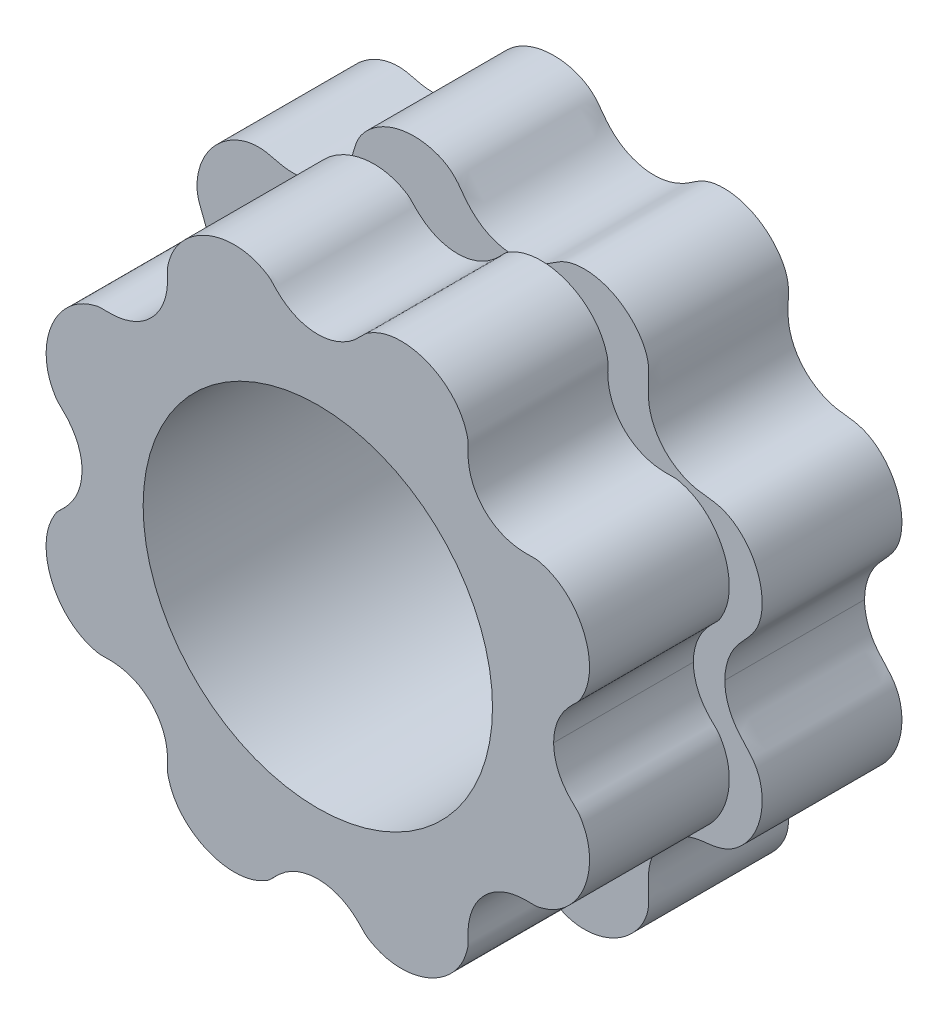
SolidWorks part; units mm, degrees
ref_plane "Plan de face" through (0, 0, 0) normal (0, 0, 1) x (1, 0, 0)
ref_plane "Plan de dessus" through (0, 0, 0) normal (0, 1, 0) x (1, 0, 0)
ref_plane "Plan de droite" through (0, 0, 0) normal (1, 0, 0) x (0, 0, -1)
sketch "Esquisse1" plane through (0, 0, 0) normal (0, 0, 1) x (1, 0, 0)
  line L0 (-1000, 0) -> (49000, 0) construction
  spline S0 degree 4 poles (8.7803, 2.0844) (8.759, 1.978) (8.7116, 1.8178) (8.6208, 1.6087) (8.4352, 1.3623) (8.2291, 1.1723) (8.0546, 0.9611) (7.9309, 0.754) (7.8577, 0.5838) (7.8163, 0.4608) (7.7897, 0.3601) (7.7696, 0.2597) (7.7562, 0.1563) (7.7491, 0.0328) (7.7496, -0.0491) (7.7588, -0.1913) (7.7779, -0.3065) (7.8056, -0.4254) (7.841, -0.5373) (7.8831, -0.6437) (7.9405, -0.7643) (8.0051, -0.8752) (8.0749, -0.9763) (8.1479, -1.0682) (8.2211, -1.1528) (8.3136, -1.2502) (8.4331, -1.3675) (8.5597, -1.5239) (8.6668, -1.7139) (8.7499, -1.9332) (8.8131, -2.2165) (8.8306, -2.5628) (8.778, -2.9416) (8.6388, -3.3355) (8.4213, -3.7041) (8.1416, -4.0116) (7.8245, -4.2297) (7.4913, -4.3566) (7.1957, -4.385) (6.9323, -4.4107) (6.6448, -4.4834) (6.3462, -4.6152) (6.0562, -4.8275) (5.8056, -5.1258) (5.6474, -5.4483) (5.5685, -5.7654) (5.5509, -6.0274) (5.559, -6.2259) (5.5768, -6.424) (5.5841, -6.6544) (5.5247, -6.9709) (5.364, -7.3215) (5.1104, -7.6501) (4.7959, -7.9189) (4.46, -8.1128) (4.07, -8.2508) (3.6586, -8.3061) (3.2746, -8.27) (2.9708, -8.1632) (2.775, -8.0416) (2.6123, -7.9272) (2.4444, -7.8209) (2.2088, -7.7052) (1.8946, -7.6149) (1.5364, -7.5907) (1.1524, -7.6584) (0.8241, -7.8037) (0.5597, -7.996) (0.3779, -8.1853) (0.2565, -8.3426) (0.1428, -8.5058) (0.0003, -8.687) (-0.2486, -8.8913) (-0.5971, -9.0565) (-1.0026, -9.1453) (-1.4163, -9.149) (-1.7983, -9.0816) (-2.1858, -8.9366) (-2.5365, -8.7145) (-2.8074, -8.4401) (-2.9714, -8.1629) (-3.0433, -7.944) (-3.0944, -7.7517) (-3.1547, -7.5624) (-3.2608, -7.3223) (-3.4435, -7.0512) (-3.7022, -6.8024) (-4.04, -6.6075) (-4.3848, -6.5077) (-4.711, -6.4851) (-4.9719, -6.5132) (-5.166, -6.5557) (-5.358, -6.6076) (-5.5836, -6.6548) (-5.9057, -6.6513) (-6.2788, -6.5539) (-6.6465, -6.3612) (-6.9658, -6.0981) (-7.2151, -5.801) (-7.4187, -5.4409) (-7.5446, -5.0453) (-7.5758, -4.661) (-7.5233, -4.3432) (-7.4376, -4.1292) (-7.3531, -3.9491) (-7.2776, -3.7654) (-7.2046, -3.5133) (-7.1703, -3.1881) (-7.2096, -2.8216) (-7.3528, -2.4379) (-7.5822, -2.113) (-7.8731, -1.8612) (-8.1648, -1.6988) (-8.4272, -1.5882) (-8.635, -1.4411) (-8.7928, -1.2863) (-8.9216, -1.1185) (-9.0241, -0.9478) (-9.1056, -0.7696) (-9.1676, -0.5968) (-9.2112, -0.4121) (-9.2383, -0.2591) (-9.2499, -0.0714) (-9.2511, 0.0231) (-9.2456, 0.1474) (-9.236, 0.2528) (-9.2216, 0.3507) (-9.2023, 0.4489) (-9.1722, 0.5713) (-9.1226, 0.7275) (-9.0436, 0.9139) (-8.9291, 1.1109) (-8.7889, 1.2906) (-8.642, 1.4324) (-8.4961, 1.5394) (-8.3465, 1.6201) (-8.2018, 1.6867) (-8.0955, 1.7412) (-8.0264, 1.7808) (-7.9923, 1.8014) knots 0 0 0 0 0 0.012017 0.018525 0.025033 0.034045 0.043057 0.048815 0.051694 0.054573 0.057453 0.060333 0.063213 0.066093 0.069526 0.072959 0.076393 0.079826 0.08291 0.085994 0.089079 0.094647 0.097131 0.099614 0.102098 0.107066 0.112033 0.118191 0.124349 0.131165 0.13798 0.150298 0.162615 0.173316 0.184016 0.19759 0.208293 0.215687 0.22308 0.230394 0.237707 0.24842 0.259137 0.269855 0.280567 0.287881 0.295194 0.298891 0.302588 0.309981 0.320684 0.334258 0.344959 0.355659 0.36636 0.37706 0.390635 0.401338 0.408731 0.412428 0.416125 0.423438 0.430751 0.441464 0.452182 0.462899 0.473612 0.480925 0.488239 0.491935 0.495632 0.503026 0.513729 0.527303 0.538003 0.548704 0.559404 0.570105 0.583679 0.594382 0.601775 0.605472 0.609169 0.616482 0.623796 0.634508 0.645226 0.655944 0.666656 0.67397 0.681283 0.68498 0.688676 0.69607 0.706773 0.720347 0.731048 0.741748 0.752449 0.763149 0.776723 0.787426 0.79482 0.798517 0.802213 0.809527 0.81684 0.827553 0.83827 0.850051 0.861806 0.871198 0.880589 0.886967 0.893346 0.899224 0.905101 0.910307 0.915512 0.920718 0.925923 0.930358 0.934792 0.937583 0.940373 0.943163 0.945953 0.948743 0.951534 0.957114 0.964137 0.97116 0.976742 0.982324 0.986743 0.991162 0.995581 1 1 1 1 1 construction
  spline S1 degree 4 poles (7.75, 0) (7.75, -0.0269) (7.7516, -0.0801) (7.7588, -0.1913) (7.7779, -0.3065) (7.8056, -0.4254) (7.841, -0.5373) (7.8831, -0.6437) (7.9405, -0.7643) (8.0051, -0.8752) (8.0749, -0.9763) (8.1479, -1.0682) (8.2211, -1.1528) (8.3136, -1.2502) (8.4331, -1.3675) (8.5597, -1.5239) (8.6668, -1.7139) (8.7499, -1.9332) (8.8131, -2.2165) (8.8306, -2.5628) (8.778, -2.9416) (8.6388, -3.3355) (8.4213, -3.7041) (8.1416, -4.0116) (7.8245, -4.2297) (7.4913, -4.3566) (7.1957, -4.385) (6.9323, -4.4107) (6.6448, -4.4834) (6.3462, -4.6152) (6.0562, -4.8275) (5.8056, -5.1258) (5.6474, -5.4483) (5.5685, -5.7654) (5.5509, -6.0274) (5.559, -6.2259) (5.5768, -6.424) (5.5841, -6.6544) (5.5247, -6.9709) (5.364, -7.3215) (5.1104, -7.6501) (4.7959, -7.9189) (4.46, -8.1128) (4.07, -8.2508) (3.6586, -8.3061) (3.2746, -8.27) (2.9708, -8.1632) (2.775, -8.0416) (2.6123, -7.9272) (2.4444, -7.8209) (2.2088, -7.7052) (1.8946, -7.6149) (1.5364, -7.5907) (1.1524, -7.6584) (0.8241, -7.8037) (0.5597, -7.996) (0.3779, -8.1853) (0.2565, -8.3426) (0.1428, -8.5058) (0.0003, -8.687) (-0.2486, -8.8913) (-0.5971, -9.0565) (-1.0026, -9.1453) (-1.4163, -9.149) (-1.7983, -9.0816) (-2.1858, -8.9366) (-2.5365, -8.7145) (-2.8074, -8.4401) (-2.9714, -8.1629) (-3.0433, -7.944) (-3.0944, -7.7517) (-3.1547, -7.5624) (-3.2608, -7.3223) (-3.4435, -7.0512) (-3.7022, -6.8024) (-4.04, -6.6075) (-4.3848, -6.5077) (-4.711, -6.4851) (-4.9719, -6.5132) (-5.166, -6.5557) (-5.358, -6.6076) (-5.5836, -6.6548) (-5.9057, -6.6513) (-6.2788, -6.5539) (-6.6465, -6.3612) (-6.9658, -6.0981) (-7.2151, -5.801) (-7.4187, -5.4409) (-7.5446, -5.0453) (-7.5758, -4.661) (-7.5233, -4.3432) (-7.4376, -4.1292) (-7.3531, -3.9491) (-7.2776, -3.7654) (-7.2046, -3.5133) (-7.1703, -3.1881) (-7.2096, -2.8216) (-7.3528, -2.4379) (-7.5822, -2.113) (-7.8731, -1.8612) (-8.1648, -1.6988) (-8.4272, -1.5882) (-8.635, -1.4411) (-8.7928, -1.2863) (-8.9216, -1.1185) (-9.0241, -0.9478) (-9.1056, -0.7696) (-9.1676, -0.5968) (-9.2112, -0.4121) (-9.2383, -0.2591) (-9.248, -0.1025) (-9.25, -0.0347) (-9.25, 0) knots 0.066093 0.066093 0.066093 0.066093 0.066093 0.069526 0.072959 0.076393 0.079826 0.08291 0.085994 0.089079 0.094647 0.097131 0.099614 0.102098 0.107066 0.112033 0.118191 0.124349 0.131165 0.13798 0.150298 0.162615 0.173316 0.184016 0.19759 0.208293 0.215687 0.22308 0.230394 0.237707 0.24842 0.259137 0.269855 0.280567 0.287881 0.295194 0.298891 0.302588 0.309981 0.320684 0.334258 0.344959 0.355659 0.36636 0.37706 0.390635 0.401338 0.408731 0.412428 0.416125 0.423438 0.430751 0.441464 0.452182 0.462899 0.473612 0.480925 0.488239 0.491935 0.495632 0.503026 0.513729 0.527303 0.538003 0.548704 0.559404 0.570105 0.583679 0.594382 0.601775 0.605472 0.609169 0.616482 0.623796 0.634508 0.645226 0.655944 0.666656 0.67397 0.681283 0.68498 0.688676 0.69607 0.706773 0.720347 0.731048 0.741748 0.752449 0.763149 0.776723 0.787426 0.79482 0.798517 0.802213 0.809527 0.81684 0.827553 0.83827 0.850051 0.861806 0.871198 0.880589 0.886967 0.893346 0.899224 0.905101 0.910307 0.915512 0.920718 0.925923 0.930358 0.934792 0.934792 0.934792 0.934792 0.934792 construction
  spline S2 degree 4 poles (7.75, 0) (7.75, 0.0269) (7.7516, 0.0801) (7.7588, 0.1913) (7.7779, 0.3065) (7.8056, 0.4254) (7.841, 0.5373) (7.8831, 0.6437) (7.9405, 0.7643) (8.0051, 0.8752) (8.0749, 0.9763) (8.1479, 1.0682) (8.2211, 1.1528) (8.3136, 1.2502) (8.4331, 1.3675) (8.5597, 1.5239) (8.6668, 1.7139) (8.7499, 1.9332) (8.8131, 2.2165) (8.8306, 2.5628) (8.778, 2.9416) (8.6388, 3.3355) (8.4213, 3.7041) (8.1416, 4.0116) (7.8245, 4.2297) (7.4913, 4.3566) (7.1957, 4.385) (6.9323, 4.4107) (6.6448, 4.4834) (6.3462, 4.6152) (6.0562, 4.8275) (5.8056, 5.1258) (5.6474, 5.4483) (5.5685, 5.7654) (5.5509, 6.0274) (5.559, 6.2259) (5.5768, 6.424) (5.5841, 6.6544) (5.5247, 6.9709) (5.364, 7.3215) (5.1104, 7.6501) (4.7959, 7.9189) (4.46, 8.1128) (4.07, 8.2508) (3.6586, 8.3061) (3.2746, 8.27) (2.9708, 8.1632) (2.775, 8.0416) (2.6123, 7.9272) (2.4444, 7.8209) (2.2088, 7.7052) (1.8946, 7.6149) (1.5364, 7.5907) (1.1524, 7.6584) (0.8241, 7.8037) (0.5597, 7.996) (0.3779, 8.1853) (0.2565, 8.3426) (0.1428, 8.5058) (0.0003, 8.687) (-0.2486, 8.8913) (-0.5971, 9.0565) (-1.0026, 9.1453) (-1.4163, 9.149) (-1.7983, 9.0816) (-2.1858, 8.9366) (-2.5365, 8.7145) (-2.8074, 8.4401) (-2.9714, 8.1629) (-3.0433, 7.944) (-3.0944, 7.7517) (-3.1547, 7.5624) (-3.2608, 7.3223) (-3.4435, 7.0512) (-3.7022, 6.8024) (-4.04, 6.6075) (-4.3848, 6.5077) (-4.711, 6.4851) (-4.9719, 6.5132) (-5.166, 6.5557) (-5.358, 6.6076) (-5.5836, 6.6548) (-5.9057, 6.6513) (-6.2788, 6.5539) (-6.6465, 6.3612) (-6.9658, 6.0981) (-7.2151, 5.801) (-7.4187, 5.4409) (-7.5446, 5.0453) (-7.5758, 4.661) (-7.5233, 4.3432) (-7.4376, 4.1292) (-7.3531, 3.9491) (-7.2776, 3.7654) (-7.2046, 3.5133) (-7.1703, 3.1881) (-7.2096, 2.8216) (-7.3528, 2.4379) (-7.5822, 2.113) (-7.8731, 1.8612) (-8.1648, 1.6988) (-8.4272, 1.5882) (-8.635, 1.4411) (-8.7928, 1.2863) (-8.9216, 1.1185) (-9.0241, 0.9478) (-9.1056, 0.7696) (-9.1676, 0.5968) (-9.2112, 0.4121) (-9.2383, 0.2591) (-9.248, 0.1025) (-9.25, 0.0347) (-9.25, 0) knots 0.066093 0.066093 0.066093 0.066093 0.066093 0.069526 0.072959 0.076393 0.079826 0.08291 0.085994 0.089079 0.094647 0.097131 0.099614 0.102098 0.107066 0.112033 0.118191 0.124349 0.131165 0.13798 0.150298 0.162615 0.173316 0.184016 0.19759 0.208293 0.215687 0.22308 0.230394 0.237707 0.24842 0.259137 0.269855 0.280567 0.287881 0.295194 0.298891 0.302588 0.309981 0.320684 0.334258 0.344959 0.355659 0.36636 0.37706 0.390635 0.401338 0.408731 0.412428 0.416125 0.423438 0.430751 0.441464 0.452182 0.462899 0.473612 0.480925 0.488239 0.491935 0.495632 0.503026 0.513729 0.527303 0.538003 0.548704 0.559404 0.570105 0.583679 0.594382 0.601775 0.605472 0.609169 0.616482 0.623796 0.634508 0.645226 0.655944 0.666656 0.67397 0.681283 0.68498 0.688676 0.69607 0.706773 0.720347 0.731048 0.741748 0.752449 0.763149 0.776723 0.787426 0.79482 0.798517 0.802213 0.809527 0.81684 0.827553 0.83827 0.850051 0.861806 0.871198 0.880589 0.886967 0.893346 0.899224 0.905101 0.910307 0.915512 0.920718 0.925923 0.930358 0.934792 0.934792 0.934792 0.934792 0.934792 construction
  spline S3 degree 1 poles (7.65, 0) (-9.15, 0) knots 0 0 1 1 construction
  spline S4 degree 1 poles (7.65, 0) (-9.15, 0) knots 0 0 1 1 construction
  spline S5 degree 3 poles (7.65, 0) (7.65, 0.3408) (7.8098, 0.8699) (8.2973, 1.3646) (8.6717, 1.828) (8.7831, 2.6376) (8.5305, 3.3888) (8.1407, 3.8756) (7.7627, 4.1565) (7.3383, 4.2872) (6.6589, 4.3181) (5.8584, 4.7576) (5.453, 5.5666) (5.4572, 6.2693) (5.5047, 6.879) (5.1067, 7.5875) (4.4533, 8.036) (3.848, 8.1914) (3.3794, 8.1898) (2.9459, 8.0584) (2.5618, 7.7538) (2.0783, 7.5424) (1.383, 7.4623) (0.7011, 7.7054) (0.2114, 8.2113) (-0.1292, 8.7502) (-0.8552, 9.0773) (-1.6511, 9.0424) (-2.2286, 8.802) (-2.6017, 8.5215) (-2.8866, 8.1566) (-2.9939, 7.7006) (-3.1913, 7.2112) (-3.6388, 6.6728) (-4.2986, 6.3773) (-5.0016, 6.3971) (-5.4766, 6.5533) (-5.925, 6.5512) (-6.52, 6.3553) (-7.0089, 5.9463) (-7.3258, 5.4066) (-7.4571, 4.9596) (-7.4718, 4.4901) (-7.3011, 4.0739) (-7.1001, 3.5882) (-7.0658, 3.0647) (-7.1841, 2.5522) (-7.4539, 2.1016) (-7.8414, 1.7461) (-8.3141, 1.5373) (-8.6819, 1.2898) (-9.0415, 0.7761) (-9.15, 0.307) (-9.15, 0) knots 0.066093 0.066093 0.066093 0.066093 0.09324 0.106813 0.120387 0.147533 0.17468 0.188254 0.201827 0.215401 0.228974 0.256121 0.283268 0.296841 0.310415 0.337561 0.364708 0.378282 0.391855 0.405429 0.419002 0.432576 0.446149 0.473296 0.486869 0.500443 0.52759 0.554736 0.56831 0.581883 0.595457 0.60903 0.622604 0.636177 0.663324 0.676897 0.690471 0.704044 0.717618 0.744764 0.758338 0.771911 0.785485 0.799058 0.812632 0.826205 0.839778 0.853352 0.866925 0.880499 0.894072 0.907646 0.934792 0.934792 0.934792 0.934792
  spline S6 degree 3 poles (-9.15, 0) (-9.15, -0.307) (-9.0415, -0.7761) (-8.6819, -1.2898) (-8.3141, -1.5373) (-7.8414, -1.7461) (-7.4539, -2.1016) (-7.1841, -2.5522) (-7.0658, -3.0647) (-7.1001, -3.5882) (-7.3011, -4.0739) (-7.4718, -4.4901) (-7.4571, -4.9596) (-7.3258, -5.4066) (-7.0089, -5.9463) (-6.52, -6.3553) (-5.925, -6.5512) (-5.4766, -6.5533) (-5.0016, -6.3971) (-4.2986, -6.3773) (-3.6388, -6.6728) (-3.1913, -7.2112) (-2.9939, -7.7006) (-2.8866, -8.1566) (-2.6017, -8.5215) (-2.2286, -8.802) (-1.6511, -9.0424) (-0.8552, -9.0773) (-0.1292, -8.7502) (0.2114, -8.2113) (0.7011, -7.7054) (1.383, -7.4623) (2.0783, -7.5424) (2.5618, -7.7538) (2.9459, -8.0584) (3.3794, -8.1898) (3.848, -8.1914) (4.4533, -8.036) (5.1067, -7.5875) (5.5047, -6.879) (5.4572, -6.2693) (5.453, -5.5666) (5.8584, -4.7576) (6.6589, -4.3181) (7.3383, -4.2872) (7.7627, -4.1565) (8.1407, -3.8756) (8.5305, -3.3888) (8.7831, -2.6376) (8.6717, -1.828) (8.2973, -1.3646) (7.8098, -0.8699) (7.65, -0.3408) (7.65, 0) knots 0.066093 0.066093 0.066093 0.066093 0.09324 0.106813 0.120387 0.13396 0.147533 0.161107 0.17468 0.188254 0.201827 0.215401 0.228974 0.242547 0.256121 0.283268 0.296841 0.310415 0.323988 0.337561 0.364708 0.378282 0.391855 0.405429 0.419002 0.432576 0.446149 0.473296 0.500443 0.514016 0.52759 0.554736 0.56831 0.581883 0.595457 0.60903 0.622604 0.636177 0.663324 0.690471 0.704044 0.717618 0.744764 0.771911 0.785485 0.799058 0.812632 0.826205 0.853352 0.880499 0.894072 0.907646 0.934792 0.934792 0.934792 0.934792
  dimension "D2" = 0.1
extrude "Boss.-Extru.4" add sketch "Esquisse1" along normal blind 4
sketch "Esquisse3" plane through (0, 0, 4) normal (0, 0, 1) x (1, 0, 0)
  line L0 (-1000, 0) -> (49000, 0) construction
  spline S0 degree 4 poles (7.6487, 1.7197) (7.6397, 1.6979) (7.6209, 1.6547) (7.5905, 1.5907) (7.5449, 1.5086) (7.4945, 1.4152) (7.4156, 1.3285) (7.3207, 1.2433) (7.2229, 1.1446) (7.1213, 1.0311) (7.022, 0.8979) (6.9433, 0.7673) (6.8836, 0.6419) (6.8431, 0.538) (6.8166, 0.4579) (6.7944, 0.3761) (6.7766, 0.2945) (6.7631, 0.2088) (6.7541, 0.1312) (6.7495, 0.0278) (6.7497, -0.0349) (6.755, -0.1463) (6.7659, -0.2288) (6.7823, -0.3252) (6.8041, -0.4141) (6.8312, -0.505) (6.8638, -0.5929) (6.9206, -0.7239) (7.0139, -0.8909) (7.1289, -1.0461) (7.2627, -1.1858) (7.368, -1.2868) (7.4406, -1.3539) (7.5056, -1.4337) (7.5559, -1.528) (7.6216, -1.6501) (7.6947, -1.8258) (7.7568, -2.0554) (7.7966, -2.4362) (7.7454, -2.8544) (7.5976, -3.2677) (7.3603, -3.6343) (7.1292, -3.8825) (6.911, -4.0477) (6.7294, -4.1486) (6.5829, -4.211) (6.4776, -4.2466) (6.3715, -4.2786) (6.2628, -4.3043) (6.1509, -4.3009) (6.0404, -4.2985) (5.9239, -4.2978) (5.8026, -4.3041) (5.6436, -4.3223) (5.4229, -4.3705) (5.155, -4.4742) (4.8654, -4.6639) (4.6419, -4.9004) (4.4944, -5.1337) (4.3922, -5.3665) (4.3272, -5.5934) (4.2993, -5.8053) (4.2972, -5.9963) (4.3013, -6.1603) (4.3052, -6.2826) (4.2677, -6.4051) (4.2302, -6.531) (4.1885, -6.638) (4.12, -6.7845) (4.0111, -6.9637) (3.787, -7.2391) (3.4519, -7.4995) (3.0502, -7.6876) (2.6199, -7.7764) (2.3177, -7.7846) (2.076, -7.7554) (1.9043, -7.7148) (1.7805, -7.6742) (1.6679, -7.6286) (1.5679, -7.5773) (1.4654, -7.524) (1.3669, -7.457) (1.2857, -7.3653) (1.1987, -7.277) (1.1097, -7.1899) (1.015, -7.1102) (0.9159, -7.0363) (0.8118, -6.9702) (0.6463, -6.8813) (0.41, -6.7909) (0.1026, -6.7349) (-0.2229, -6.7528) (-0.488, -6.8195) (-0.7192, -6.9154) (-0.8907, -7.015) (-1.0429, -7.1291) (-1.182, -7.2587) (-1.2787, -7.3583) (-1.3626, -7.4521) (-1.4589, -7.5196) (-1.5486, -7.567) (-1.6436, -7.6173) (-1.7485, -7.6619) (-1.9044, -7.7167) (-2.1159, -7.7653) (-2.4808, -7.7964) (-2.9052, -7.733) (-3.313, -7.5746) (-3.6656, -7.3338) (-3.8974, -7.1111) (-4.0687, -6.8803) (-4.1744, -6.6805) (-4.2373, -6.5108) (-4.2742, -6.3839) (-4.3003, -6.2855) (-4.3025, -6.1875) (-4.2996, -6.0941) (-4.2976, -5.9894) (-4.2995, -5.8738) (-4.3116, -5.7131) (-4.3434, -5.5336) (-4.3989, -5.3495) (-4.4996, -5.1248) (-4.6481, -4.8926) (-4.8426, -4.689) (-5.0764, -4.5257) (-5.316, -4.4107) (-5.5431, -4.3383) (-5.7566, -4.3039) (-5.9497, -4.2969) (-6.0992, -4.2993) (-6.2053, -4.3041) (-6.3143, -4.2957) (-6.4213, -4.2629) (-6.558, -4.222) (-6.7391, -4.1467) (-6.952, -4.0228) (-7.1878, -3.827) (-7.4065, -3.5709) (-7.5838, -3.2732) (-7.7111, -2.9408) (-7.7764, -2.6074) (-7.785, -2.284) (-7.7441, -1.9963) (-7.6775, -1.7765) (-7.6005, -1.6085) (-7.534, -1.4869) (-7.4778, -1.3922) (-7.3995, -1.3162) (-7.3222, -1.2428) (-7.2415, -1.1638) (-7.1612, -1.0767) (-7.0826, -0.9803) (-7.0081, -0.8737) (-6.947, -0.7706) (-6.898, -0.6726) (-6.8592, -0.5812) (-6.829, -0.4974) (-6.8032, -0.4111) (-6.7821, -0.3226) (-6.7659, -0.2313) (-6.755, -0.1423) (-6.7484, -0.0133) (-6.7502, 0.0591) (-6.7598, 0.2021) (-6.7799, 0.3082) (-6.8089, 0.4423) (-6.8572, 0.5815) (-6.9324, 0.751) (-7.022, 0.8967) (-7.1213, 1.0319) (-7.2229, 1.1442) (-7.3207, 1.2436) (-7.4156, 1.3284) (-7.4945, 1.4153) (-7.5449, 1.5086) (-7.5905, 1.5907) (-7.6209, 1.6547) (-7.6397, 1.6979) (-7.6487, 1.7197) knots 0 0 0 0 0 0.002971 0.005941 0.008912 0.011882 0.016256 0.02063 0.025004 0.029378 0.035458 0.041538 0.044198 0.046857 0.049517 0.052177 0.054837 0.057497 0.060158 0.062818 0.06575 0.068682 0.071614 0.074546 0.077511 0.080477 0.083443 0.086408 0.095483 0.104557 0.107667 0.110776 0.113886 0.116995 0.120592 0.124189 0.131384 0.140925 0.150466 0.172222 0.183937 0.195652 0.205212 0.214772 0.218272 0.221773 0.225273 0.228773 0.232271 0.235769 0.239267 0.242765 0.246927 0.25109 0.259415 0.271179 0.282914 0.294344 0.300072 0.3058 0.314901 0.324001 0.326913 0.329824 0.335648 0.339256 0.342863 0.34647 0.350078 0.359646 0.369213 0.391031 0.402991 0.414951 0.424282 0.428948 0.433613 0.437157 0.4407 0.444244 0.447788 0.451711 0.455635 0.459558 0.463482 0.467365 0.471248 0.47513 0.479013 0.49103 0.503006 0.514154 0.519741 0.525328 0.534497 0.539082 0.543666 0.549255 0.55205 0.554844 0.558433 0.562022 0.565611 0.5692 0.57925 0.5893 0.611553 0.62268 0.633806 0.642852 0.651897 0.658762 0.662195 0.665627 0.668578 0.671529 0.67448 0.677431 0.681767 0.686104 0.694778 0.700357 0.705936 0.717086 0.729368 0.735527 0.741686 0.750505 0.759325 0.76267 0.766015 0.769361 0.772706 0.776376 0.780045 0.787384 0.797351 0.807318 0.818484 0.829649 0.840815 0.85198 0.861108 0.870237 0.877296 0.880825 0.884355 0.887728 0.8911 0.894473 0.897846 0.901942 0.906038 0.910135 0.914231 0.917037 0.919843 0.922648 0.925454 0.928386 0.931318 0.93425 0.937182 0.942503 0.945163 0.947823 0.953143 0.958462 0.964542 0.970622 0.974996 0.97937 0.983744 0.988118 0.991088 0.994059 0.997029 1 1 1 1 1 construction
  spline S1 degree 4 poles (6.75, 0) (6.75, -0.0203) (6.7509, -0.0607) (6.755, -0.1463) (6.7659, -0.2288) (6.7823, -0.3252) (6.8041, -0.4141) (6.8312, -0.505) (6.8638, -0.5929) (6.9206, -0.7239) (7.0139, -0.8909) (7.1289, -1.0461) (7.2627, -1.1858) (7.368, -1.2868) (7.4406, -1.3539) (7.5056, -1.4337) (7.5559, -1.528) (7.6216, -1.6501) (7.6947, -1.8258) (7.7568, -2.0554) (7.7966, -2.4362) (7.7454, -2.8544) (7.5976, -3.2677) (7.3603, -3.6343) (7.1292, -3.8825) (6.911, -4.0477) (6.7294, -4.1486) (6.5829, -4.211) (6.4776, -4.2466) (6.3715, -4.2786) (6.2628, -4.3043) (6.1509, -4.3009) (6.0404, -4.2985) (5.9239, -4.2978) (5.8026, -4.3041) (5.6436, -4.3223) (5.4229, -4.3705) (5.155, -4.4742) (4.8654, -4.6639) (4.6419, -4.9004) (4.4944, -5.1337) (4.3922, -5.3665) (4.3272, -5.5934) (4.2993, -5.8053) (4.2972, -5.9963) (4.3013, -6.1603) (4.3052, -6.2826) (4.2677, -6.4051) (4.2302, -6.531) (4.1885, -6.638) (4.12, -6.7845) (4.0111, -6.9637) (3.787, -7.2391) (3.4519, -7.4995) (3.0502, -7.6876) (2.6199, -7.7764) (2.3177, -7.7846) (2.076, -7.7554) (1.9043, -7.7148) (1.7805, -7.6742) (1.6679, -7.6286) (1.5679, -7.5773) (1.4654, -7.524) (1.3669, -7.457) (1.2857, -7.3653) (1.1987, -7.277) (1.1097, -7.1899) (1.015, -7.1102) (0.9159, -7.0363) (0.8118, -6.9702) (0.6463, -6.8813) (0.41, -6.7909) (0.1026, -6.7349) (-0.2229, -6.7528) (-0.488, -6.8195) (-0.7192, -6.9154) (-0.8907, -7.015) (-1.0429, -7.1291) (-1.182, -7.2587) (-1.2787, -7.3583) (-1.3626, -7.4521) (-1.4589, -7.5196) (-1.5486, -7.567) (-1.6436, -7.6173) (-1.7485, -7.6619) (-1.9044, -7.7167) (-2.1159, -7.7653) (-2.4808, -7.7964) (-2.9052, -7.733) (-3.313, -7.5746) (-3.6656, -7.3338) (-3.8974, -7.1111) (-4.0687, -6.8803) (-4.1744, -6.6805) (-4.2373, -6.5108) (-4.2742, -6.3839) (-4.3003, -6.2855) (-4.3025, -6.1875) (-4.2996, -6.0941) (-4.2976, -5.9894) (-4.2995, -5.8738) (-4.3116, -5.7131) (-4.3434, -5.5336) (-4.3989, -5.3495) (-4.4996, -5.1248) (-4.6481, -4.8926) (-4.8426, -4.689) (-5.0764, -4.5257) (-5.316, -4.4107) (-5.5431, -4.3383) (-5.7566, -4.3039) (-5.9497, -4.2969) (-6.0992, -4.2993) (-6.2053, -4.3041) (-6.3143, -4.2957) (-6.4213, -4.2629) (-6.558, -4.222) (-6.7391, -4.1467) (-6.952, -4.0228) (-7.1878, -3.827) (-7.4065, -3.5709) (-7.5838, -3.2732) (-7.7111, -2.9408) (-7.7764, -2.6074) (-7.785, -2.284) (-7.7441, -1.9963) (-7.6775, -1.7765) (-7.6005, -1.6085) (-7.534, -1.4869) (-7.4778, -1.3922) (-7.3995, -1.3162) (-7.3222, -1.2428) (-7.2415, -1.1638) (-7.1612, -1.0767) (-7.0826, -0.9803) (-7.0081, -0.8737) (-6.947, -0.7706) (-6.898, -0.6726) (-6.8592, -0.5812) (-6.829, -0.4974) (-6.8032, -0.4111) (-6.7821, -0.3226) (-6.7659, -0.2313) (-6.755, -0.1423) (-6.7509, -0.0619) (-6.75, -0.0203) (-6.75, 0) knots 0.062818 0.062818 0.062818 0.062818 0.062818 0.06575 0.068682 0.071614 0.074546 0.077511 0.080477 0.083443 0.086408 0.095483 0.104557 0.107667 0.110776 0.113886 0.116995 0.120592 0.124189 0.131384 0.140925 0.150466 0.172222 0.183937 0.195652 0.205212 0.214772 0.218272 0.221773 0.225273 0.228773 0.232271 0.235769 0.239267 0.242765 0.246927 0.25109 0.259415 0.271179 0.282914 0.294344 0.300072 0.3058 0.314901 0.324001 0.326913 0.329824 0.335648 0.339256 0.342863 0.34647 0.350078 0.359646 0.369213 0.391031 0.402991 0.414951 0.424282 0.428948 0.433613 0.437157 0.4407 0.444244 0.447788 0.451711 0.455635 0.459558 0.463482 0.467365 0.471248 0.47513 0.479013 0.49103 0.503006 0.514154 0.519741 0.525328 0.534497 0.539082 0.543666 0.549255 0.55205 0.554844 0.558433 0.562022 0.565611 0.5692 0.57925 0.5893 0.611553 0.62268 0.633806 0.642852 0.651897 0.658762 0.662195 0.665627 0.668578 0.671529 0.67448 0.677431 0.681767 0.686104 0.694778 0.700357 0.705936 0.717086 0.729368 0.735527 0.741686 0.750505 0.759325 0.76267 0.766015 0.769361 0.772706 0.776376 0.780045 0.787384 0.797351 0.807318 0.818484 0.829649 0.840815 0.85198 0.861108 0.870237 0.877296 0.880825 0.884355 0.887728 0.8911 0.894473 0.897846 0.901942 0.906038 0.910135 0.914231 0.917037 0.919843 0.922648 0.925454 0.928386 0.931318 0.93425 0.937182 0.937182 0.937182 0.937182 0.937182
  spline S2 degree 4 poles (6.75, 0) (6.75, 0.0203) (6.7509, 0.0607) (6.755, 0.1463) (6.7659, 0.2288) (6.7823, 0.3252) (6.8041, 0.4141) (6.8312, 0.505) (6.8638, 0.5929) (6.9206, 0.7239) (7.0139, 0.8909) (7.1289, 1.0461) (7.2627, 1.1858) (7.368, 1.2868) (7.4406, 1.3539) (7.5056, 1.4337) (7.5559, 1.528) (7.6216, 1.6501) (7.6947, 1.8258) (7.7568, 2.0554) (7.7966, 2.4362) (7.7454, 2.8544) (7.5976, 3.2677) (7.3603, 3.6343) (7.1292, 3.8825) (6.911, 4.0477) (6.7294, 4.1486) (6.5829, 4.211) (6.4776, 4.2466) (6.3715, 4.2786) (6.2628, 4.3043) (6.1509, 4.3009) (6.0404, 4.2985) (5.9239, 4.2978) (5.8026, 4.3041) (5.6436, 4.3223) (5.4229, 4.3705) (5.155, 4.4742) (4.8654, 4.6639) (4.6419, 4.9004) (4.4944, 5.1337) (4.3922, 5.3665) (4.3272, 5.5934) (4.2993, 5.8053) (4.2972, 5.9963) (4.3013, 6.1603) (4.3052, 6.2826) (4.2677, 6.4051) (4.2302, 6.531) (4.1885, 6.638) (4.12, 6.7845) (4.0111, 6.9637) (3.787, 7.2391) (3.4519, 7.4995) (3.0502, 7.6876) (2.6199, 7.7764) (2.3177, 7.7846) (2.076, 7.7554) (1.9043, 7.7148) (1.7805, 7.6742) (1.6679, 7.6286) (1.5679, 7.5773) (1.4654, 7.524) (1.3669, 7.457) (1.2857, 7.3653) (1.1987, 7.277) (1.1097, 7.1899) (1.015, 7.1102) (0.9159, 7.0363) (0.8118, 6.9702) (0.6463, 6.8813) (0.41, 6.7909) (0.1026, 6.7349) (-0.2229, 6.7528) (-0.488, 6.8195) (-0.7192, 6.9154) (-0.8907, 7.015) (-1.0429, 7.1291) (-1.182, 7.2587) (-1.2787, 7.3583) (-1.3626, 7.4521) (-1.4589, 7.5196) (-1.5486, 7.567) (-1.6436, 7.6173) (-1.7485, 7.6619) (-1.9044, 7.7167) (-2.1159, 7.7653) (-2.4808, 7.7964) (-2.9052, 7.733) (-3.313, 7.5746) (-3.6656, 7.3338) (-3.8974, 7.1111) (-4.0687, 6.8803) (-4.1744, 6.6805) (-4.2373, 6.5108) (-4.2742, 6.3839) (-4.3003, 6.2855) (-4.3025, 6.1875) (-4.2996, 6.0941) (-4.2976, 5.9894) (-4.2995, 5.8738) (-4.3116, 5.7131) (-4.3434, 5.5336) (-4.3989, 5.3495) (-4.4996, 5.1248) (-4.6481, 4.8926) (-4.8426, 4.689) (-5.0764, 4.5257) (-5.316, 4.4107) (-5.5431, 4.3383) (-5.7566, 4.3039) (-5.9497, 4.2969) (-6.0992, 4.2993) (-6.2053, 4.3041) (-6.3143, 4.2957) (-6.4213, 4.2629) (-6.558, 4.222) (-6.7391, 4.1467) (-6.952, 4.0228) (-7.1878, 3.827) (-7.4065, 3.5709) (-7.5838, 3.2732) (-7.7111, 2.9408) (-7.7764, 2.6074) (-7.785, 2.284) (-7.7441, 1.9963) (-7.6775, 1.7765) (-7.6005, 1.6085) (-7.534, 1.4869) (-7.4778, 1.3922) (-7.3995, 1.3162) (-7.3222, 1.2428) (-7.2415, 1.1638) (-7.1612, 1.0767) (-7.0826, 0.9803) (-7.0081, 0.8737) (-6.947, 0.7706) (-6.898, 0.6726) (-6.8592, 0.5812) (-6.829, 0.4974) (-6.8032, 0.4111) (-6.7821, 0.3226) (-6.7659, 0.2313) (-6.755, 0.1423) (-6.7509, 0.0619) (-6.75, 0.0203) (-6.75, 0) knots 0.062818 0.062818 0.062818 0.062818 0.062818 0.06575 0.068682 0.071614 0.074546 0.077511 0.080477 0.083443 0.086408 0.095483 0.104557 0.107667 0.110776 0.113886 0.116995 0.120592 0.124189 0.131384 0.140925 0.150466 0.172222 0.183937 0.195652 0.205212 0.214772 0.218272 0.221773 0.225273 0.228773 0.232271 0.235769 0.239267 0.242765 0.246927 0.25109 0.259415 0.271179 0.282914 0.294344 0.300072 0.3058 0.314901 0.324001 0.326913 0.329824 0.335648 0.339256 0.342863 0.34647 0.350078 0.359646 0.369213 0.391031 0.402991 0.414951 0.424282 0.428948 0.433613 0.437157 0.4407 0.444244 0.447788 0.451711 0.455635 0.459558 0.463482 0.467365 0.471248 0.47513 0.479013 0.49103 0.503006 0.514154 0.519741 0.525328 0.534497 0.539082 0.543666 0.549255 0.55205 0.554844 0.558433 0.562022 0.565611 0.5692 0.57925 0.5893 0.611553 0.62268 0.633806 0.642852 0.651897 0.658762 0.662195 0.665627 0.668578 0.671529 0.67448 0.677431 0.681767 0.686104 0.694778 0.700357 0.705936 0.717086 0.729368 0.735527 0.741686 0.750505 0.759325 0.76267 0.766015 0.769361 0.772706 0.776376 0.780045 0.787384 0.797351 0.807318 0.818484 0.829649 0.840815 0.85198 0.861108 0.870237 0.877296 0.880825 0.884355 0.887728 0.8911 0.894473 0.897846 0.901942 0.906038 0.910135 0.914231 0.917037 0.919843 0.922648 0.925454 0.928386 0.931318 0.93425 0.937182 0.937182 0.937182 0.937182 0.937182
extrude "Boss.-Extru.5" add sketch "Esquisse3" along normal blind 4
sketch "Esquisse4" plane through (0, 0, 0) normal (0, 0, -1) x (-1, 0, 0)
  circle A0 centre (0, 0) radius 5
  dimension "D1" = 10
extrude "Enlèv. mat.-Extru.1" cut sketch "Esquisse4" against normal through all
equation "\"R\"= 10'Radius of the rotor"
equation "\"E\"= 0.75'Eccentricity from input shaft to center of rotor"
equation "\"Rr\"= 1.5'Roller radius"
equation "\"N\"= 10'Amount of rollers"
equation "\"R2\"= 9"
equation "\"N2\"= 9"
